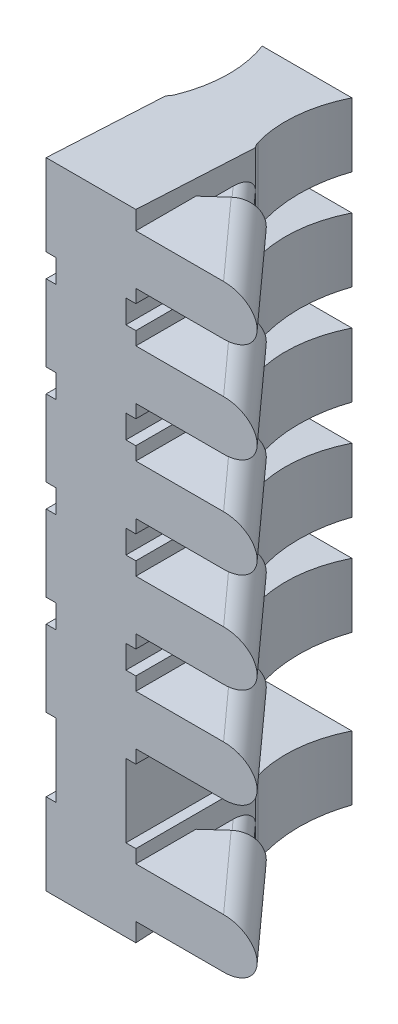
SolidWorks part; units mm, degrees
ref_plane "Front Plane" through (0, 0, 0) normal (0, 0, 1) x (1, 0, 0)
ref_plane "Top Plane" through (0, 0, 0) normal (0, 1, 0) x (1, 0, 0)
ref_plane "Right Plane" through (0, 0, 0) normal (1, 0, 0) x (0, 0, -1)
sketch "Sketch1" plane through (0, 0, 0) normal (0, 0, 1) x (1, 0, 0)
  line L0 (-7.5, 0) -> (0, 0) construction
  line L1 (-7.5, 15) -> (7.5, 15)
  line L2 (-7.5, 15) -> (-7.5, -15)
  line L3 (-7.5, -15) -> (7.5, -15)
  line L4 (7.5, 15) -> (7.5, -15)
  line L5 (0, 0) -> (0, 15) construction
  dimension "D1" = 15
  dimension "D2" = 30
sketch "Sketch2" plane through (0, 0, 0) normal (1, 0, 0) x (0, 0, -1)
  line L1 (0, 15) -> (7, 15)
  line L2 (0, 15) -> (0, -15)
  line L3 (0, -15) -> (7, -15)
  line L4 (7, 15) -> (7, -15)
  dimension "D1" = 7
extrude "Boss-Extrude1" add sketch "Sketch1" against normal up to vertex (7 mm away) up to point (0, 15, -7)
ref_plane "Plane1" through (1.35, 0, 0) normal (1, 0, 0) x (0, 0, -1)
sketch "Sketch7" plane through (1.35, 0, 0) normal (1, 0, 0) x (0, 0, -1)
  line L0 (3, 4.1005) -> (0, 4.1005) construction
  line L1 (0, 4.1005) -> (0, 6.3995) construction
  line L2 (3, 6.3995) -> (0, 6.3995) construction
  line L3 (3, 6.3995) -> (6.5, 6.2161) construction
  line L4 (6.5, 6.2161) -> (6.5, 4.2839) construction
  line L5 (6.5, 4.2839) -> (3, 4.1005) construction
  line L6 (3, 1.1005) -> (0, 1.1005) construction
  line L7 (0, 1.1005) -> (0, 3.3995) construction
  line L8 (3, 3.3995) -> (0, 3.3995) construction
  line L9 (6.5, 3.2161) -> (3, 3.3995) construction
  line L10 (6.5, 1.2839) -> (6.5, 3.2161) construction
  line L11 (3, 1.1005) -> (6.5, 1.2839) construction
  line L12 (3, -1.8995) -> (0, -1.8995) construction
  line L13 (0, -1.8995) -> (0, 0.3995) construction
  line L14 (3, 0.3995) -> (0, 0.3995) construction
  line L15 (3, 0.3995) -> (6.5, 0.2161) construction
  line L16 (6.5, 0.2161) -> (6.5, -1.7161) construction
  line L17 (6.5, -1.7161) -> (3, -1.8995) construction
  line L19 (3, -4.8995) -> (0, -4.8995) construction
  line L20 (0, -4.8995) -> (0, -2.6005) construction
  line L21 (3, -2.6005) -> (0, -2.6005) construction
  line L22 (6.5, -2.7839) -> (3, -2.6005) construction
  line L23 (6.5, -4.7161) -> (6.5, -2.7839) construction
  line L24 (3, -4.8995) -> (6.5, -4.7161) construction
  line L25 (3, -7.1005) -> (0, -7.1005) construction
  line L26 (0, -9.5567) -> (0, -7.1005) construction
  line L27 (6.5, -9.2161) -> (0, -9.5567) construction
  line L28 (6.5, -7.2839) -> (6.5, -9.2161) construction
  line L29 (3, -7.1005) -> (6.5, -7.2839) construction
  line L30 (3, 7.1005) -> (0, 7.1005) construction
  line L31 (0, 7.1005) -> (0, 9.5567) construction
  line L32 (6.5, 9.2161) -> (0, 9.5567) construction
  line L33 (6.5, 7.2839) -> (6.5, 9.2161) construction
  line L34 (3, 7.1005) -> (6.5, 7.2839) construction
  line L35 (3, 4.1005) -> (0, 4.1005)
  line L36 (0, 4.1005) -> (0, 6.3995)
  line L37 (3, 6.3995) -> (0, 6.3995)
  line L38 (3, 6.3995) -> (6.5, 6.2161)
  line L39 (6.5, 6.2161) -> (6.5, 4.2839)
  line L40 (6.5, 4.2839) -> (3, 4.1005)
  line L41 (3, 1.1005) -> (0, 1.1005)
  line L42 (0, 1.1005) -> (0, 3.3995)
  line L43 (3, 3.3995) -> (0, 3.3995)
  line L44 (6.5, 3.2161) -> (3, 3.3995)
  line L45 (6.5, 1.2839) -> (6.5, 3.2161)
  line L46 (3, 1.1005) -> (6.5, 1.2839)
  line L47 (3, -1.8995) -> (0, -1.8995)
  line L48 (0, -1.8995) -> (0, 0.3995)
  line L49 (3, 0.3995) -> (0, 0.3995)
  line L50 (3, 0.3995) -> (6.5, 0.2161)
  line L51 (6.5, 0.2161) -> (6.5, -1.7161)
  line L52 (6.5, -1.7161) -> (3, -1.8995)
  line L54 (3, -4.8995) -> (0, -4.8995)
  line L55 (0, -4.8995) -> (0, -2.6005)
  line L56 (3, -2.6005) -> (0, -2.6005)
  line L57 (6.5, -2.7839) -> (3, -2.6005)
  line L58 (6.5, -4.7161) -> (6.5, -2.7839)
  line L59 (3, -4.8995) -> (6.5, -4.7161)
  line L60 (3, -7.1005) -> (0, -7.1005)
  line L61 (0, -9.5567) -> (0, -7.1005)
  line L62 (6.5, -9.2161) -> (0, -9.5567)
  line L63 (6.5, -7.2839) -> (6.5, -9.2161)
  line L64 (3, -7.1005) -> (6.5, -7.2839)
  line L65 (3, 7.1005) -> (0, 7.1005)
  line L66 (0, 7.1005) -> (0, 9.5567)
  line L67 (6.5, 9.2161) -> (0, 9.5567)
  line L68 (6.5, 7.2839) -> (6.5, 9.2161)
  line L69 (3, 7.1005) -> (6.5, 7.2839)
sketch "Sketch8" plane through (1.35, 0, 0) normal (1, 0, 0) x (0, 0, -1)
  line L0 (6.5, -4.7161) -> (6.5, -2.7839) construction
  line L1 (6.5, -2.7839) -> (3, -2.6005) construction
  line L2 (3, -2.6005) -> (3, -1.8995) construction
  line L3 (6.5, -1.7161) -> (3, -1.8995) construction
  line L4 (6.5, 0.2161) -> (6.5, -1.7161) construction
  line L5 (3, 0.3995) -> (6.5, 0.2161) construction
  line L6 (3, 0.3995) -> (3, 1.1005) construction
  line L7 (3, 1.1005) -> (6.5, 1.2839) construction
  line L8 (6.5, 1.2839) -> (6.5, 3.2161) construction
  line L9 (6.5, 3.2161) -> (3, 3.3995) construction
  line L10 (3, 3.3995) -> (3, 4.1005) construction
  line L11 (6.5, 4.2839) -> (3, 4.1005) construction
  line L12 (6.5, 6.2161) -> (6.5, 4.2839) construction
  line L13 (3, 6.3995) -> (6.5, 6.2161) construction
  line L14 (3, 6.3995) -> (3, 7.1005) construction
  line L15 (3, 7.1005) -> (6.5, 7.2839) construction
  line L16 (6.5, 7.2839) -> (6.5, 9.2161) construction
  line L17 (6.5, 9.2161) -> (0, 9.5567) construction
  line L18 (0, 9.5567) -> (0, -9.5567) construction
  line L19 (6.5, -9.2161) -> (0, -9.5567) construction
  line L20 (6.5, -7.2839) -> (6.5, -9.2161) construction
  line L21 (3, -7.1005) -> (6.5, -7.2839) construction
  line L22 (3, -7.1005) -> (3, -4.8995) construction
  line L23 (3, -4.8995) -> (6.5, -4.7161) construction
  line L24 (6.5, -4.7161) -> (6.5, -2.7839)
  line L25 (6.5, -2.7839) -> (3, -2.6005)
  line L26 (3, -2.6005) -> (3, -1.8995)
  line L27 (6.5, -1.7161) -> (3, -1.8995)
  line L28 (6.5, 0.2161) -> (6.5, -1.7161)
  line L29 (3, 0.3995) -> (6.5, 0.2161)
  line L30 (3, 0.3995) -> (3, 1.1005)
  line L31 (3, 1.1005) -> (6.5, 1.2839)
  line L32 (6.5, 1.2839) -> (6.5, 3.2161)
  line L33 (6.5, 3.2161) -> (3, 3.3995)
  line L34 (3, 3.3995) -> (3, 4.1005)
  line L35 (6.5, 4.2839) -> (3, 4.1005)
  line L36 (6.5, 6.2161) -> (6.5, 4.2839)
  line L37 (3, 6.3995) -> (6.5, 6.2161)
  line L38 (3, 6.3995) -> (3, 7.1005)
  line L39 (3, 7.1005) -> (6.5, 7.2839)
  line L40 (6.5, 7.2839) -> (6.5, 9.2161)
  line L41 (6.5, 9.2161) -> (0, 9.5567)
  line L42 (0, 9.5567) -> (0, -9.5567)
  line L43 (6.5, -9.2161) -> (0, -9.5567)
  line L44 (6.5, -7.2839) -> (6.5, -9.2161)
  line L45 (3, -7.1005) -> (6.5, -7.2839)
  line L46 (3, -7.1005) -> (3, -4.8995)
  line L47 (3, -4.8995) -> (6.5, -4.7161)
sketch "Sketch9" plane through (0, 0, 0) normal (0, 0, 1) x (1, 0, 0)
  line L0 (-1.35, 9.5567) -> (-1.35, -9.5567) construction
  line L1 (1.35, -9.5567) -> (-1.35, -9.5567) construction
  line L2 (1.35, 9.5567) -> (1.35, -9.5567) construction
  line L3 (1.35, 9.5567) -> (-1.35, 9.5567) construction
  line L4 (-1.35, 9.5567) -> (-1.35, -9.5567) construction
  line L5 (1.35, -9.5567) -> (-1.35, -9.5567) construction
  line L6 (1.35, 9.5567) -> (1.35, -9.5567) construction
  line L7 (1.35, 9.5567) -> (-1.35, 9.5567) construction
  line L8 (0, -9.5567) -> (0, 9.5567) construction
  line L9 (-1.35, 0) -> (1.35, 0) construction
  line L10 (0.75, -9.1562) -> (-0.75, -9.1562) construction
  line L11 (-0.75, 9.1562) -> (-0.75, -9.1562) construction
  line L12 (0.75, 9.1562) -> (-0.75, 9.1562) construction
  line L13 (0.75, -9.1562) -> (-0.75, -9.1562)
  line L14 (-0.75, 9.1562) -> (-0.75, -9.1562)
  line L15 (0.75, 9.1562) -> (-0.75, 9.1562)
  line L16 (0.75, -9.1562) -> (0.75, 9.1562)
  line L17 (1.05, -9.5567) -> (1.05, 9.5567) construction
  line L18 (-1.05, -9.5567) -> (-1.05, 9.5567) construction
  line L19 (1.05, -9.5567) -> (1.05, 9.5567) construction
  line L20 (-1.05, -9.5567) -> (-1.05, 9.5567) construction
ref_plane "Plane2" through (0, -9.5567, 0) normal (0, 1, 0) x (1, 0, 0)
sketch "Sketch10" plane through (0, -9.5567, 0) normal (0, 1, 0) x (1, 0, 0)
  line L0 (1.35, 3.5995) -> (1.35, 6.5)
  line L1 (-1.35, 3.5995) -> (-1.35, 6.5)
  arc A0 (-1.2465, 3.7776) -> (-1.35, 6.5) centre (-4.95, 5) ccw construction
  arc A1 (-1.35, 3.5995) -> (-1.2465, 3.7776) centre (-1.7213, 3.9344) ccw construction
  arc A2 (1.2465, 3.7776) -> (1.35, 3.5995) centre (1.7213, 3.9344) ccw construction
  arc A3 (1.35, 6.5) -> (1.2465, 3.7776) centre (4.95, 5) ccw construction
  arc A4 (-1.2465, 3.7776) -> (-1.35, 6.5) centre (-4.95, 5) ccw
  arc A5 (-1.35, 3.5995) -> (-1.2465, 3.7776) centre (-1.7213, 3.9344) ccw
  arc A6 (1.2465, 3.7776) -> (1.35, 3.5995) centre (1.7213, 3.9344) ccw
  arc A7 (1.35, 6.5) -> (1.2465, 3.7776) centre (4.95, 5) ccw
ref_plane "Plane3" through (2.213, 9.1562, -4.3777) normal (0.6697, 0, 0.7426) x (0, -1, 0)
sketch "Sketch11" plane through (2.213, 9.1562, -4.3777) normal (0.6697, 0, 0.7426) x (0, -1, 0)
  line L0 (0.4562, -2.362) -> (0.4562, -1.612) construction
  line L1 (1.3562, -1.612) -> (1.3562, -2.362) construction
  line L2 (1.3562, -2.362) -> (0.4562, -2.362) construction
  line L3 (3.4562, -1.612) -> (3.4562, -2.362) construction
  line L4 (3.4562, -2.362) -> (4.3562, -2.362) construction
  line L5 (4.3562, -2.362) -> (4.3562, -1.612) construction
  line L6 (7.3562, -1.612) -> (7.3562, -2.362) construction
  line L7 (7.3562, -2.362) -> (6.4562, -2.362) construction
  line L8 (6.4562, -2.362) -> (6.4562, -1.612) construction
  line L9 (9.4562, -1.612) -> (9.4562, -2.362) construction
  line L10 (9.4562, -2.362) -> (10.3562, -2.362) construction
  line L11 (10.3562, -2.362) -> (10.3562, -1.612) construction
  line L12 (13.3562, -1.612) -> (13.3562, -2.362) construction
  line L13 (13.3562, -2.362) -> (12.4562, -2.362) construction
  line L14 (12.4562, -2.362) -> (12.4562, -1.612) construction
  line L15 (16.9562, -1.612) -> (16.9562, -2.362) construction
  line L16 (16.9562, -2.362) -> (17.8562, -2.362) construction
  line L17 (17.8562, -2.362) -> (17.8562, -1.612) construction
  line L18 (0.4562, -2.362) -> (0.4562, -1.612)
  line L19 (1.3562, -1.612) -> (1.3562, -2.362)
  line L20 (1.3562, -2.362) -> (0.4562, -2.362)
  line L21 (3.4562, -1.612) -> (3.4562, -2.362)
  line L22 (3.4562, -2.362) -> (4.3562, -2.362)
  line L23 (4.3562, -2.362) -> (4.3562, -1.612)
  line L24 (7.3562, -1.612) -> (7.3562, -2.362)
  line L25 (7.3562, -2.362) -> (6.4562, -2.362)
  line L26 (6.4562, -2.362) -> (6.4562, -1.612)
  line L27 (9.4562, -1.612) -> (9.4562, -2.362)
  line L28 (9.4562, -2.362) -> (10.3562, -2.362)
  line L29 (10.3562, -2.362) -> (10.3562, -1.612)
  line L30 (13.3562, -1.612) -> (13.3562, -2.362)
  line L31 (13.3562, -2.362) -> (12.4562, -2.362)
  line L32 (12.4562, -2.362) -> (12.4562, -1.612)
  line L33 (16.9562, -1.612) -> (16.9562, -2.362)
  line L34 (16.9562, -2.362) -> (17.8562, -2.362)
  line L35 (17.8562, -2.362) -> (17.8562, -1.612)
  arc A0 (1.3562, -1.612) -> (0.4562, -1.612) centre (0.9062, -1.612) ccw construction
  arc A1 (4.3562, -1.612) -> (3.4562, -1.612) centre (3.9062, -1.612) ccw construction
  arc A2 (7.3562, -1.612) -> (6.4562, -1.612) centre (6.9062, -1.612) ccw construction
  arc A3 (10.3562, -1.612) -> (9.4562, -1.612) centre (9.9062, -1.612) ccw construction
  arc A4 (13.3562, -1.612) -> (12.4562, -1.612) centre (12.9062, -1.612) ccw construction
  arc A5 (17.8562, -1.612) -> (16.9562, -1.612) centre (17.4062, -1.612) ccw construction
  arc A6 (1.3562, -1.612) -> (0.4562, -1.612) centre (0.9062, -1.612) ccw
  arc A7 (4.3562, -1.612) -> (3.4562, -1.612) centre (3.9062, -1.612) ccw
  arc A8 (7.3562, -1.612) -> (6.4562, -1.612) centre (6.9062, -1.612) ccw
  arc A9 (10.3562, -1.612) -> (9.4562, -1.612) centre (9.9062, -1.612) ccw
  arc A10 (13.3562, -1.612) -> (12.4562, -1.612) centre (12.9062, -1.612) ccw
  arc A11 (17.8562, -1.612) -> (16.9562, -1.612) centre (17.4062, -1.612) ccw
ref_plane "Plane4" through (3.1041, 9.1562, -3.3895) normal (0.6697, 0, 0.7426) x (0, -1, 0)
sketch "Sketch12" plane through (3.1041, 9.1562, -3.3895) normal (0.6697, 0, 0.7426) x (0, -1, 0)
  line L0 (0.1562, -1.612) -> (0.1562, -5.0612) construction
  line L1 (0.1562, -5.0612) -> (1.6562, -5.0612) construction
  line L2 (1.6562, -1.612) -> (1.6562, -5.0612) construction
  line L3 (3.1562, -1.612) -> (3.1562, -5.0612) construction
  line L4 (4.6562, -5.0612) -> (3.1562, -5.0612) construction
  line L5 (4.6562, -1.612) -> (4.6562, -5.0612) construction
  line L6 (6.1562, -1.612) -> (6.1562, -5.0612) construction
  line L7 (6.1562, -5.0612) -> (7.6562, -5.0612) construction
  line L8 (7.6562, -1.612) -> (7.6562, -5.0612) construction
  line L9 (9.1562, -1.612) -> (9.1562, -5.0612) construction
  line L10 (10.6562, -5.0612) -> (9.1562, -5.0612) construction
  line L11 (10.6562, -1.612) -> (10.6562, -5.0612) construction
  line L12 (12.1562, -1.612) -> (12.1562, -5.0612) construction
  line L13 (12.1562, -5.0612) -> (13.6562, -5.0612) construction
  line L14 (13.6562, -1.612) -> (13.6562, -5.0612) construction
  line L15 (16.6562, -1.612) -> (16.6562, -5.0612) construction
  line L16 (18.1562, -5.0612) -> (16.6562, -5.0612) construction
  line L17 (18.1562, -1.612) -> (18.1562, -5.0612) construction
  line L18 (0.1562, -1.612) -> (0.1562, -5.0612)
  line L19 (0.1562, -5.0612) -> (1.6562, -5.0612)
  line L20 (1.6562, -1.612) -> (1.6562, -5.0612)
  line L21 (3.1562, -1.612) -> (3.1562, -5.0612)
  line L22 (4.6562, -5.0612) -> (3.1562, -5.0612)
  line L23 (4.6562, -1.612) -> (4.6562, -5.0612)
  line L24 (6.1562, -1.612) -> (6.1562, -5.0612)
  line L25 (6.1562, -5.0612) -> (7.6562, -5.0612)
  line L26 (7.6562, -1.612) -> (7.6562, -5.0612)
  line L27 (9.1562, -1.612) -> (9.1562, -5.0612)
  line L28 (10.6562, -5.0612) -> (9.1562, -5.0612)
  line L29 (10.6562, -1.612) -> (10.6562, -5.0612)
  line L30 (12.1562, -1.612) -> (12.1562, -5.0612)
  line L31 (12.1562, -5.0612) -> (13.6562, -5.0612)
  line L32 (13.6562, -1.612) -> (13.6562, -5.0612)
  line L33 (16.6562, -1.612) -> (16.6562, -5.0612)
  line L34 (18.1562, -5.0612) -> (16.6562, -5.0612)
  line L35 (18.1562, -1.612) -> (18.1562, -5.0612)
  arc A0 (1.6562, -1.612) -> (0.1562, -1.612) centre (0.9062, -1.612) ccw construction
  arc A1 (4.6562, -1.612) -> (3.1562, -1.612) centre (3.9062, -1.612) ccw construction
  arc A2 (7.6562, -1.612) -> (6.1562, -1.612) centre (6.9062, -1.612) ccw construction
  arc A3 (10.6562, -1.612) -> (9.1562, -1.612) centre (9.9062, -1.612) ccw construction
  arc A4 (13.6562, -1.612) -> (12.1562, -1.612) centre (12.9062, -1.612) ccw construction
  arc A5 (18.1562, -1.612) -> (16.6562, -1.612) centre (17.4062, -1.612) ccw construction
  arc A6 (1.6562, -1.612) -> (0.1562, -1.612) centre (0.9062, -1.612) ccw
  arc A7 (4.6562, -1.612) -> (3.1562, -1.612) centre (3.9062, -1.612) ccw
  arc A8 (7.6562, -1.612) -> (6.1562, -1.612) centre (6.9062, -1.612) ccw
  arc A9 (10.6562, -1.612) -> (9.1562, -1.612) centre (9.9062, -1.612) ccw
  arc A10 (13.6562, -1.612) -> (12.1562, -1.612) centre (12.9062, -1.612) ccw
  arc A11 (18.1562, -1.612) -> (16.6562, -1.612) centre (17.4062, -1.612) ccw
extrude "Cut-Extrude1" cut sketch "Sketch8" against normal up to vertex (2.4 mm away) from vertex at -0.3 starting at point (1.05, -9.5567, 0)
extrude "Cut-Extrude4" cut sketch "Sketch7" against normal up to vertex (2.7 mm away) up to point (-1.35, -9.5567, 0)
extrude "Boss-Extrude2" add sketch "Sketch10" along normal up to vertex (24.5567 mm away)
extrude "Cut-Extrude2" cut sketch "Sketch12" along normal through all
extrude "Cut-Extrude3" cut sketch "Sketch11" along normal through all
mirror "Mirror1" about plane through (0, 0, 0) normal (1, 0, 0) of "Cut-Extrude2", "Cut-Extrude3"
sketch "Sketch13" plane through (0, 0, 0) normal (0, 0, 1) x (1, 0, 0)
  line L0 (0, 0) -> (-5, 0) construction
  line L1 (-5, -10) -> (5, -10)
  line L2 (-5, -10) -> (-5, 10)
  line L3 (-5, 10) -> (5, 10)
  line L4 (5, -10) -> (5, 10)
  line L5 (0, 0) -> (5, 0) construction
  line L6 (0, 0) -> (0, 10) construction
  line L7 (0, 0) -> (0, -10) construction
  dimension "D1" = 20
  dimension "D2" = 10
extrude "Boss-Extrude3" add sketch "Sketch13" against normal blind 7 separate body
combine bodies "Combine1" operation type subtract main body 114 bodies to subtract 112
sketch "Sketch14" plane through (0, 0, 0) normal (0, 0, 1) x (1, 0, 0)
  line L1 (-1.35, -9.5567) -> (-5, -9.5567)
  line L2 (-1.35, -9.5567) -> (-1.35, 9.5567)
  line L3 (-1.35, 9.5567) -> (-5, 9.5567)
  line L4 (-5, -9.5567) -> (-5, 9.5567)
  ellipse E0 centre (-3.9901, 8.25) end of major axis (-2.9802, 8.25) minor radius 0.75 (-3.9901, 9) -> (-3.9901, 7.5) ccw construction
extrude "Cut-Extrude5" cut sketch "Sketch14" against normal through all
